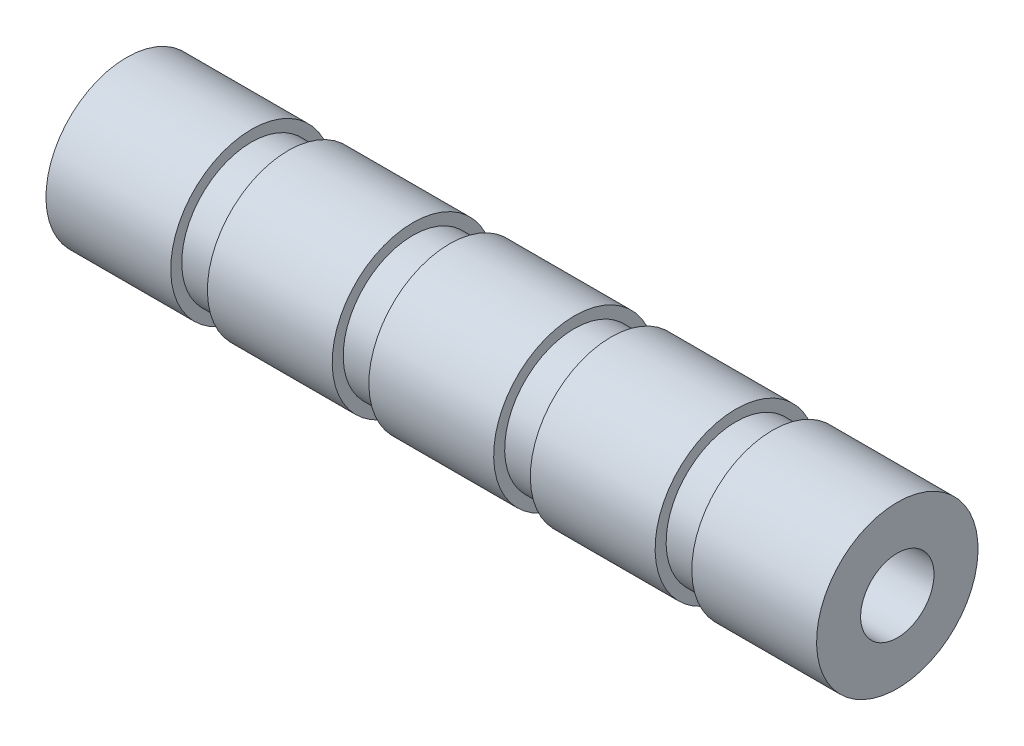
SolidWorks part; units mm, degrees
ref_plane "Front Plane" through (0, 0, 0) normal (0, 0, 1) x (1, 0, 0)
ref_plane "Top Plane" through (0, 0, 0) normal (0, 1, 0) x (1, 0, 0)
ref_plane "Right Plane" through (0, 0, 0) normal (1, 0, 0) x (0, 0, -1)
sketch "Sketch1" plane through (0, 0, 0) normal (0, 0, 1) x (1, 0, 0)
  line L0 (11, -5.5) -> (11, 5.5) construction
  line L1 (-6, -5.5) -> (11, -5.5)
  line L3 (-6, 5.5) -> (11, 5.5)
  line L5 (0, 0) -> (11, 5.5) construction
  line L6 (0, 0) -> (11, -5.5) construction
  line L12 (-6, 5.5) -> (-11, 5.5)
  line L13 (11, 5.5) -> (11, -5.5)
  line L50 (-6, -5.5) -> (-6, -4)
  line L51 (-11, -4) -> (-6, -4)
  line L54 (-11, 5.5) -> (-33, 5.5)
  line L56 (-33, -4) -> (-28, -4)
  line L57 (-28, -4) -> (-28, -5.5)
  line L58 (-28, -5.5) -> (-11, -5.5)
  line L59 (-11, -5.5) -> (-11, -4)
  line L60 (-33, 5.5) -> (-55, 5.5)
  line L62 (-55, -4) -> (-50, -4)
  line L63 (-50, -4) -> (-50, -5.5)
  line L64 (-50, -5.5) -> (-33, -5.5)
  line L65 (-33, -5.5) -> (-33, -4)
  line L66 (-55, 5.5) -> (-77, 5.5)
  line L68 (-77, -4) -> (-72, -4)
  line L69 (-72, -4) -> (-72, -5.5)
  line L70 (-72, -5.5) -> (-55, -5.5)
  line L71 (-55, -5.5) -> (-55, -4)
  line L72 (-77, 5.5) -> (-94, 5.5)
  line L73 (-94, 5.5) -> (-94, -5.5)
  line L74 (-94, -5.5) -> (-77, -5.5)
  line L75 (-77, -5.5) -> (-77, -4)
  point P0 (0, 0)
  dimension "D1" = 17
  dimension "D2" = 17
  dimension "D3" = 22
  dimension "D4" = 5
  dimension "D5" = 5
  dimension "D6" = 22
  dimension "D7" = 5
  dimension "D8" = 22
  dimension "D9" = 5
  dimension "D10" = 17
revolve "Revolve2" add sketch "Sketch1" angle 360 about L60
sketch "Sketch3" plane through (-94, 0, 0) normal (-1, 0, 0) x (0, 0, 1)
  circle A0 centre (0, 5.5) radius 5
  dimension "D1" = 10
extrude "Cut-Extrude2" cut sketch "Sketch3" against normal through all
